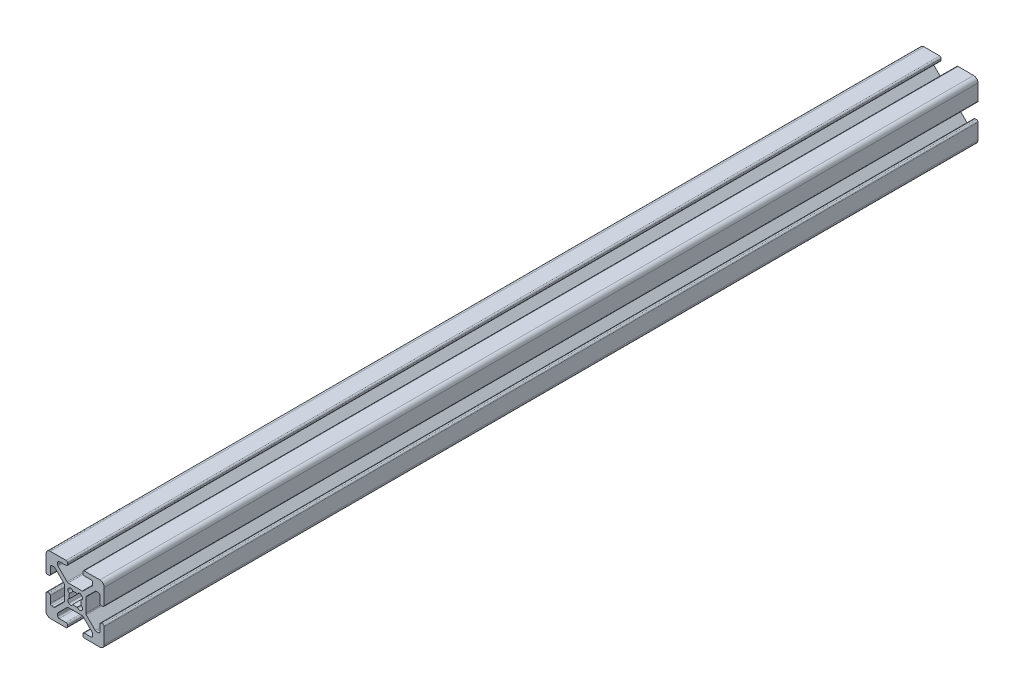
SolidWorks part; units mm, degrees
material "1060 Alloy"
ref_plane "Front Plane" through (0, 0, 0) normal (0, 0, 1) x (1, 0, 0)
ref_plane "Top Plane" through (0, 0, 0) normal (0, 1, 0) x (1, 0, 0)
ref_plane "Right Plane" through (0, 0, 0) normal (1, 0, 0) x (0, 0, -1)
sketch "Sketch2" plane through (0, 0, 0) normal (0, 0, 1) x (1, 0, 0)
  line L0 (-10, -3.138) -> (-10, -8.5)
  line L1 (-8.5, -10) -> (-3.138, -10)
  line L2 (-2.63, -9.492) -> (-2.63, -9.008)
  line L3 (-3.138, -8.5) -> (-5.487, -8.5)
  line L4 (-5.995, -7.992) -> (-5.995, -7.2662)
  line L5 (-5.8462, -6.907) -> (-2.743, -3.8038)
  line L6 (-2.3838, -3.655) -> (2.3841, -3.655)
  line L7 (2.7433, -3.8038) -> (5.8462, -6.9067)
  line L8 (5.995, -7.2659) -> (5.995, -7.992)
  line L9 (5.487, -8.5) -> (3.138, -8.5)
  line L10 (2.63, -9.008) -> (2.63, -9.492)
  line L11 (3.138, -10) -> (8.5, -10)
  line L12 (10, -8.5) -> (10, -3.138)
  line L13 (9.492, -2.63) -> (9.008, -2.63)
  line L14 (8.5, -3.138) -> (8.5, -5.487)
  line L15 (7.992, -5.995) -> (7.2662, -5.995)
  line L16 (6.907, -5.8462) -> (3.8038, -2.743)
  line L17 (3.655, -2.3838) -> (3.655, 2.3841)
  line L18 (3.8038, 2.7433) -> (6.9067, 5.8462)
  line L19 (7.2659, 5.995) -> (7.992, 5.995)
  line L20 (8.5, 5.487) -> (8.5, 3.138)
  line L21 (9.008, 2.63) -> (9.492, 2.63)
  line L22 (10, 3.138) -> (10, 8.5)
  line L23 (8.5, 10) -> (3.138, 10)
  line L24 (2.63, 9.492) -> (2.63, 9.008)
  line L25 (3.138, 8.5) -> (5.487, 8.5)
  line L26 (5.995, 7.992) -> (5.995, 7.2662)
  line L27 (5.8462, 6.907) -> (2.743, 3.8038)
  line L28 (2.3838, 3.655) -> (-2.3841, 3.655)
  line L29 (-2.7433, 3.8038) -> (-5.8462, 6.9067)
  line L30 (-5.995, 7.2659) -> (-5.995, 7.992)
  line L31 (-5.487, 8.5) -> (-3.138, 8.5)
  line L32 (-2.63, 9.008) -> (-2.63, 9.492)
  line L33 (-3.138, 10) -> (-8.5, 10)
  line L34 (-10, 8.5) -> (-10, 3.138)
  line L35 (-9.492, 2.63) -> (-9.008, 2.63)
  line L36 (-8.5, 3.138) -> (-8.5, 5.487)
  line L37 (-7.992, 5.995) -> (-7.2662, 5.995)
  line L38 (-6.907, 5.8462) -> (-3.8038, 2.743)
  line L39 (-3.655, 2.3838) -> (-3.655, -2.3841)
  line L40 (-3.8038, -2.7433) -> (-6.9067, -5.8462)
  line L41 (-7.2659, -5.995) -> (-7.992, -5.995)
  line L42 (-8.5, -5.487) -> (-8.5, -3.138)
  line L43 (-9.008, -2.63) -> (-9.492, -2.63)
  line L44 (-2.1245, 2.3045) -> (-2.3045, 2.1245)
  line L45 (2.3045, 2.1245) -> (2.1245, 2.3045)
  line L46 (2.1245, -2.3045) -> (2.3045, -2.1245)
  line L47 (-2.3045, -2.1245) -> (-2.1245, -2.3045)
  arc A0 (-10, -8.5) -> (-8.5, -10) centre (-8.5, -8.5) ccw
  arc A1 (-3.138, -10) -> (-2.63, -9.492) centre (-3.138, -9.492) ccw
  arc A2 (-2.63, -9.008) -> (-3.138, -8.5) centre (-3.138, -9.008) ccw
  arc A3 (-5.995, -7.992) -> (-5.487, -8.5) centre (-5.487, -7.992) ccw
  arc A4 (-5.8462, -6.907) -> (-5.995, -7.2662) centre (-5.487, -7.2662) ccw
  arc A5 (-2.3838, -3.655) -> (-2.743, -3.8038) centre (-2.3838, -4.163) ccw
  arc A6 (2.7433, -3.8038) -> (2.3841, -3.655) centre (2.3841, -4.163) ccw
  arc A7 (5.995, -7.2659) -> (5.8462, -6.9067) centre (5.487, -7.2659) ccw
  arc A8 (5.487, -8.5) -> (5.995, -7.992) centre (5.487, -7.992) ccw
  arc A9 (3.138, -8.5) -> (2.63, -9.008) centre (3.138, -9.008) ccw
  arc A10 (2.63, -9.492) -> (3.138, -10) centre (3.138, -9.492) ccw
  arc A11 (8.5, -10) -> (10, -8.5) centre (8.5, -8.5) ccw
  arc A12 (10, -3.138) -> (9.492, -2.63) centre (9.492, -3.138) ccw
  arc A13 (9.008, -2.63) -> (8.5, -3.138) centre (9.008, -3.138) ccw
  arc A14 (7.992, -5.995) -> (8.5, -5.487) centre (7.992, -5.487) ccw
  arc A15 (6.907, -5.8462) -> (7.2662, -5.995) centre (7.2662, -5.487) ccw
  arc A16 (3.655, -2.3838) -> (3.8038, -2.743) centre (4.163, -2.3838) ccw
  arc A17 (3.8038, 2.7433) -> (3.655, 2.3841) centre (4.163, 2.3841) ccw
  arc A18 (7.2659, 5.995) -> (6.9067, 5.8462) centre (7.2659, 5.487) ccw
  arc A19 (8.5, 5.487) -> (7.992, 5.995) centre (7.992, 5.487) ccw
  arc A20 (8.5, 3.138) -> (9.008, 2.63) centre (9.008, 3.138) ccw
  arc A21 (9.492, 2.63) -> (10, 3.138) centre (9.492, 3.138) ccw
  arc A22 (10, 8.5) -> (8.5, 10) centre (8.5, 8.5) ccw
  arc A23 (3.138, 10) -> (2.63, 9.492) centre (3.138, 9.492) ccw
  arc A24 (2.63, 9.008) -> (3.138, 8.5) centre (3.138, 9.008) ccw
  arc A25 (5.995, 7.992) -> (5.487, 8.5) centre (5.487, 7.992) ccw
  arc A26 (5.8462, 6.907) -> (5.995, 7.2662) centre (5.487, 7.2662) ccw
  arc A27 (2.3838, 3.655) -> (2.743, 3.8038) centre (2.3838, 4.163) ccw
  arc A28 (-2.7433, 3.8038) -> (-2.3841, 3.655) centre (-2.3841, 4.163) ccw
  arc A29 (-5.995, 7.2659) -> (-5.8462, 6.9067) centre (-5.487, 7.2659) ccw
  arc A30 (-5.487, 8.5) -> (-5.995, 7.992) centre (-5.487, 7.992) ccw
  arc A31 (-3.138, 8.5) -> (-2.63, 9.008) centre (-3.138, 9.008) ccw
  arc A32 (-2.63, 9.492) -> (-3.138, 10) centre (-3.138, 9.492) ccw
  arc A33 (-8.5, 10) -> (-10, 8.5) centre (-8.5, 8.5) ccw
  arc A34 (-10, 3.138) -> (-9.492, 2.63) centre (-9.492, 3.138) ccw
  arc A35 (-9.008, 2.63) -> (-8.5, 3.138) centre (-9.008, 3.138) ccw
  arc A36 (-7.992, 5.995) -> (-8.5, 5.487) centre (-7.992, 5.487) ccw
  arc A37 (-6.907, 5.8462) -> (-7.2662, 5.995) centre (-7.2662, 5.487) ccw
  arc A38 (-3.655, 2.3838) -> (-3.8038, 2.743) centre (-4.163, 2.3838) ccw
  arc A39 (-3.8038, -2.7433) -> (-3.655, -2.3841) centre (-4.163, -2.3841) ccw
  arc A40 (-7.2659, -5.995) -> (-6.9067, -5.8462) centre (-7.2659, -5.487) ccw
  arc A41 (-8.5, -5.487) -> (-7.992, -5.995) centre (-7.992, -5.487) ccw
  arc A42 (-8.5, -3.138) -> (-9.008, -2.63) centre (-9.008, -3.138) ccw
  arc A43 (-9.492, -2.63) -> (-10, -3.138) centre (-9.492, -3.138) ccw
  arc A44 (-1.9358, 0.8037) -> (-1.9358, -0.8037) centre (0, 0) ccw
  arc A45 (-2.3045, 2.1245) -> (-1.9358, 0.8037) centre (-1.748, 1.568) ccw
  arc A46 (-0.8037, 1.9358) -> (-2.1245, 2.3045) centre (-1.568, 1.748) ccw
  arc A47 (0.8037, 1.9358) -> (-0.8037, 1.9358) centre (0, 0) ccw
  arc A48 (2.1245, 2.3045) -> (0.8037, 1.9358) centre (1.568, 1.748) ccw
  arc A49 (1.9358, 0.8037) -> (2.3045, 2.1245) centre (1.748, 1.568) ccw
  arc A50 (1.9358, -0.8037) -> (1.9358, 0.8037) centre (0, 0) ccw
  arc A51 (2.3045, -2.1245) -> (1.9358, -0.8037) centre (1.748, -1.568) ccw
  arc A52 (0.8037, -1.9358) -> (2.1245, -2.3045) centre (1.568, -1.748) ccw
  arc A53 (-0.8037, -1.9358) -> (0.8037, -1.9358) centre (0, 0) ccw
  arc A54 (-2.1245, -2.3045) -> (-0.8037, -1.9358) centre (-1.568, -1.748) ccw
  arc A55 (-1.9358, -0.8037) -> (-2.3045, -2.1245) centre (-1.748, -1.568) ccw
extrude "Boss-Extrude1" add sketch "Sketch2" against normal blind 300
